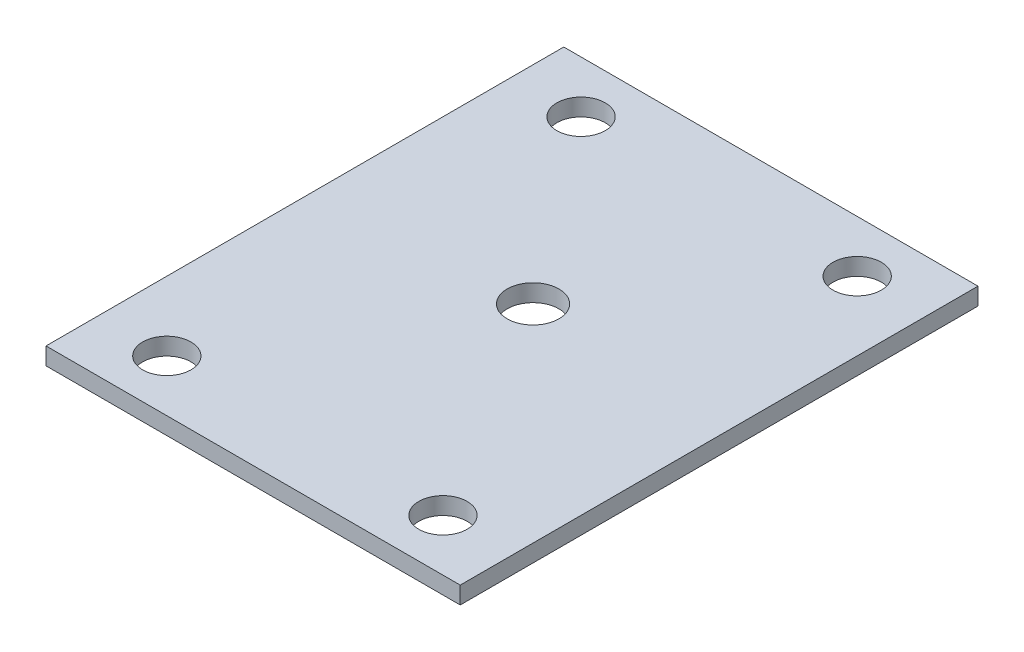
SolidWorks part; units mm, degrees
material "ABS"
ref_plane "Front Plane" through (0, 0, 0) normal (0, 0, 1) x (1, 0, 0)
ref_plane "Top Plane" through (0, 0, 0) normal (0, 1, 0) x (1, 0, 0)
ref_plane "Right Plane" through (0, 0, 0) normal (1, 0, 0) x (0, 0, -1)
sketch "Sketch1" plane through (0, 0, 0) normal (0, 1, 0) x (1, 0, 0)
  line L1 (15.24, -19.05) -> (-15.24, -19.05)
  line L2 (15.24, -19.05) -> (15.24, 19.05)
  line L3 (15.24, 19.05) -> (-15.24, 19.05)
  line L4 (-15.24, -19.05) -> (-15.24, 19.05)
  line L5 (15.24, -19.05) -> (-15.24, 19.05) construction
  line L6 (15.24, 19.05) -> (-15.24, -19.05) construction
  line L10 (-15.24, 0) -> (49984.76, 0) construction
  line L11 (0, 18.415) -> (0, -49981.585) construction
  circle A0 centre (-10.16, 15.24) radius 1.778
  circle A1 centre (10.16, 15.24) radius 1.778
  circle A2 centre (-10.16, -15.24) radius 1.778
  circle A3 centre (10.16, -15.24) radius 1.778
  point P0 (0, 0)
  point P8 (-15.24, 0)
  point P9 (15.24, 0)
  point P12 (0, 19.05)
  point P13 (0, -19.05)
  dimension "D3" = 3.556
  dimension "D4" = 30.48
  dimension "D5" = 20.32
  dimension "D1" = 38.1
  dimension "D2" = 30.48
extrude "Boss-Extrude1" add sketch "Sketch1" along normal blind 1.27
sketch "Sketch2" plane through (0, 0, 0) normal (0, -1, 0) x (1, 0, 0)
  line L0 (0, 15.24) -> (0, -49984.76) construction
  line L1 (-10.16, 15.24) -> (10.16, 15.24) construction
  line L2 (-10.16, 15.24) -> (-10.16, -15.24) construction
  line L3 (-10.16, -15.24) -> (10.16, -15.24) construction
  line L4 (10.16, 15.24) -> (10.16, -15.24) construction
  circle A0 centre (-10.16, -15.24) radius 1.778 construction
  circle A1 centre (10.16, -15.24) radius 1.778 construction
  circle A2 centre (10.16, 15.24) radius 1.778 construction
  circle A3 centre (-10.16, 15.24) radius 1.778 construction
  circle A4 centre (-10.16, -15.24) radius 1.778
  circle A5 centre (10.16, -15.24) radius 1.778
  circle A6 centre (10.16, 15.24) radius 1.778
  circle A7 centre (-10.16, 15.24) radius 1.778
  circle A8 centre (0, -1.5494) radius 1.905
  point P15 (0, -15.24)
  point P19 (0, 15.24)
  point P20 (0, 0)
  point P21 (0, 0)
  point P24 (-8.5538, -1.5494)
  dimension "D1" = 3.81
  dimension "D2" = 13.6906
extrude "Cut-Extrude1" cut sketch "Sketch2" against normal through all
